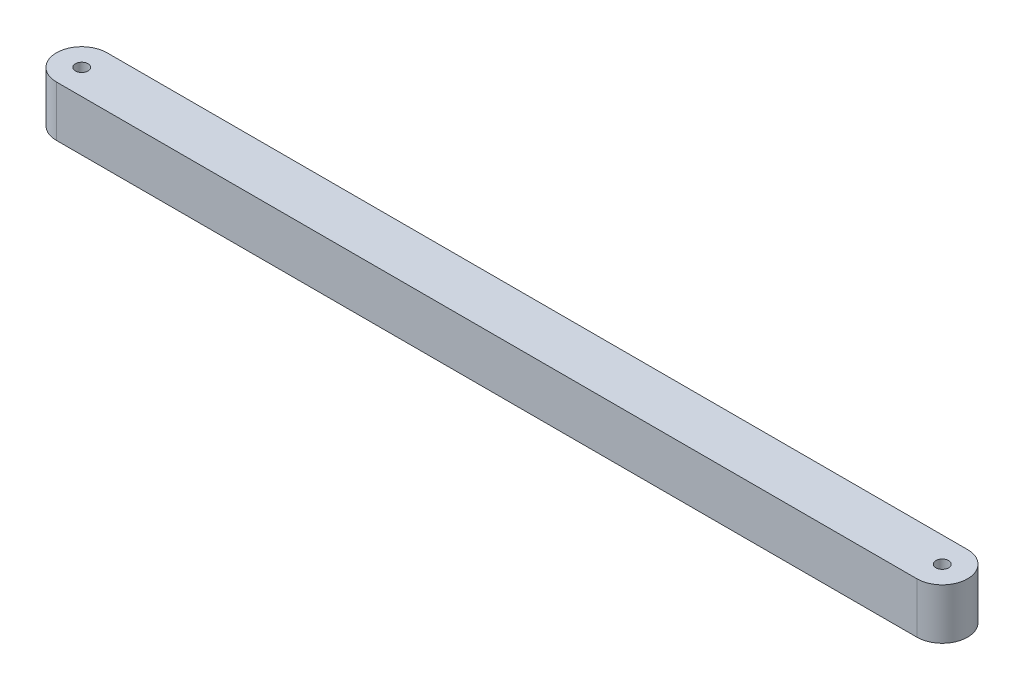
SolidWorks part; units mm, degrees
ref_plane "Front Plane" through (0, 0, 0) normal (0, 0, 1) x (1, 0, 0)
ref_plane "Top Plane" through (0, 0, 0) normal (0, 1, 0) x (1, 0, 0)
ref_plane "Right Plane" through (0, 0, 0) normal (1, 0, 0) x (0, 0, -1)
sketch "Sketch1" plane through (0, 0, 0) normal (0, 1, 0) x (1, 0, 0)
  line L1 (-431.8, -25.4) -> (431.8, -25.4)
  line L2 (-431.8, -25.4) -> (-431.8, 25.4)
  line L3 (-431.8, 25.4) -> (431.8, 25.4)
  line L4 (431.8, -25.4) -> (431.8, 25.4)
  line L5 (-431.8, -25.4) -> (431.8, 25.4) construction
  line L6 (-431.8, 25.4) -> (431.8, -25.4) construction
  arc A0 (431.8, 25.4) -> (431.8, -25.4) centre (431.8, 0) cw
  arc A1 (-431.8, 25.4) -> (-431.8, -25.4) centre (-431.8, 0) ccw
  point P0 (0, 0)
  point P7 (-457.2, 0)
  point P9 (457.2, 0)
  dimension "D1" = 50.8
  dimension "D2" = 914.4
extrude "Boss-Extrude2" add sketch "Sketch1" along normal blind 50.8 contours L2 A1 | L1 L4 L3 L2 | A0 L4
hole_wizard "1/2 (0.5) Diameter Hole1" positions "Sketch2" profile "Sketch3" hole size "1/2" standard "ANSI Inch" end condition through all
sketch "Sketch2" plane through (0, 50.8, 0) normal (0, 1, 0) x (1, 0, 0)
  point P0 (431.8, 0)
  point P3 (-431.8, 0)
sketch "Sketch3" plane through (431.8, 50.8, 0) normal (1, 0, 0) x (0, 0, 1)
  line L0 (0, 0) -> (0, 50.8)
  line L1 (0, 50.8) -> (6.35, 50.8)
  line L2 (6.35, 50.8) -> (6.35, 0)
  line L5 (6.35, 0) -> (0, 0)
  line L11 (0, -6.35) -> (0, 107.95) construction
  dimension "Thru Hole Dia." = 12.7
  dimension "Thru Hole Depth" = 50.8
